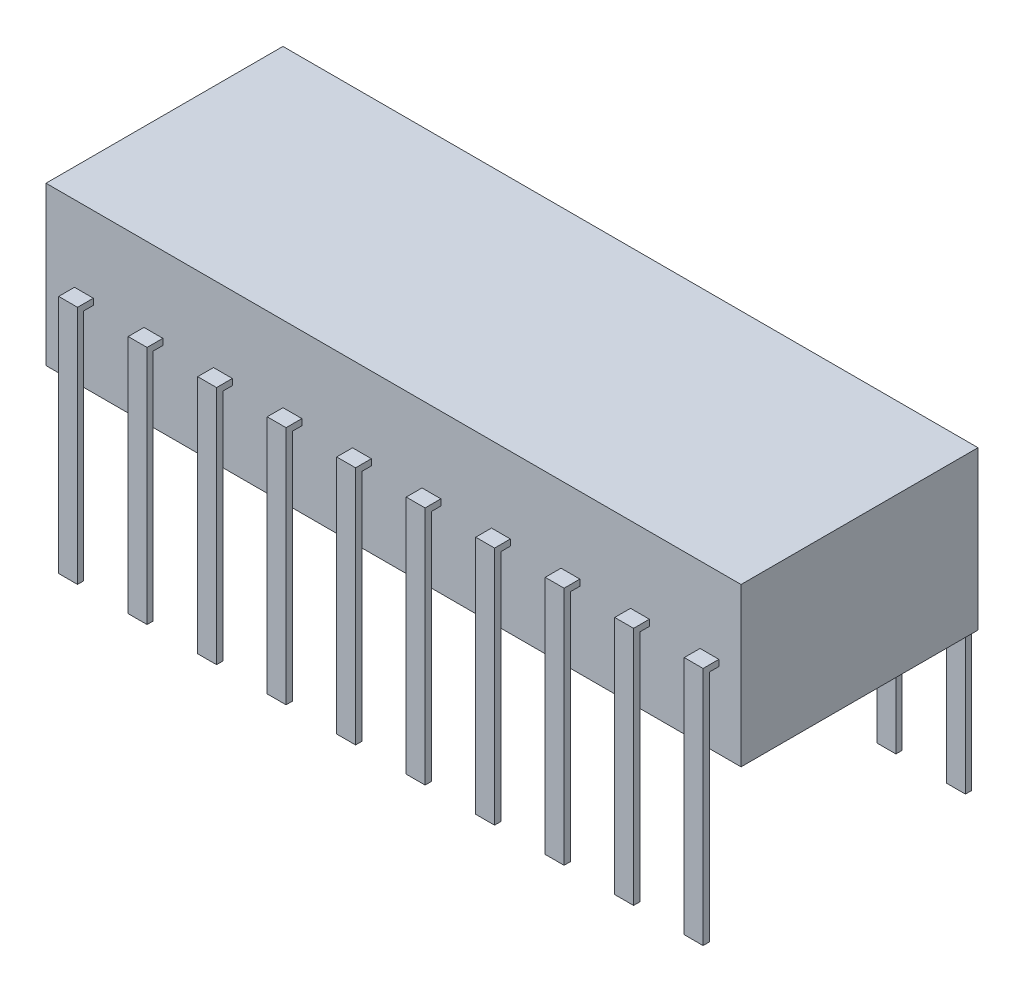
SolidWorks part; units mm, degrees
ref_plane "Front Plane" through (0, 0, 0) normal (0, 0, 1) x (1, 0, 0)
ref_plane "Top Plane" through (0, 0, 0) normal (0, 1, 0) x (1, 0, 0)
ref_plane "Right Plane" through (0, 0, 0) normal (1, 0, 0) x (0, 0, -1)
sketch "Sketch2" plane through (0, 5.9229, 0) normal (0, 0, 1) x (1, 0, 0)
  line L1 (22, 5) -> (0, 5)
  line L2 (22, 5) -> (22, 0)
  line L3 (22, 0) -> (0, 0)
  line L4 (0, 5) -> (0, 0)
  line L5 (0.7, 2.6) -> (1.3, 2.6)
  line L6 (0.7, 2.6) -> (0.7, 2.4)
  line L7 (0.7, 2.4) -> (1.3, 2.4)
  line L8 (1.3, 2.6) -> (1.3, 2.4)
extrude "Boss-Extrude2" add sketch "Sketch2" along normal blind 7.5 contours L2 L1 L4 L3
sketch "Sketch11" plane through (0, 0, 0) normal (0, 0, 1) x (1, 0, 0)
  line L1 (22, 5.9229) -> (21, 5.9229)
  line L2 (22, 5.9229) -> (22, 8.422)
  line L3 (22, 8.422) -> (21, 8.422)
  line L4 (21, 5.9229) -> (21, 8.422)
  point P5 (0, 0)
  point P6 (0, 0)
  point P7 (20.1763, 5.9229)
  point P8 (22, 5.9229)
  point P9 (22, 5.9229)
  point P10 (20.155, 6.7317)
  point P11 (20.1479, 7.0227)
  point P12 (20.4034, 8.3855)
  point P13 (19.5659, 8.5771)
  point P14 (0, 0)
  point P15 (0, 0)
  point P16 (0, 0)
sketch "Sketch16" plane through (0, 0, 0) normal (0, 0, 1) x (1, 0, 0)
  line L1 (21.2984, 8.5206) -> (20.7016, 8.5206)
  line L2 (21.2984, 8.5206) -> (21.2984, 8.3234)
  line L3 (21.2984, 8.3234) -> (20.7016, 8.3234)
  line L4 (20.7016, 8.5206) -> (20.7016, 8.3234)
  line L5 (21.2984, 8.5206) -> (20.7016, 8.3234) construction
  line L6 (21.2984, 8.3234) -> (20.7016, 8.5206) construction
  point P0 (21, 8.422)
extrude "Boss-Extrude6" add sketch "Sketch16" against normal blind 0.5
sketch "Sketch17" plane through (0, 8.3234, 0) normal (0, -1, 0) x (1, 0, 0)
  line L0 (21.2984, -0.5) -> (21.2984, 0) construction
  line L1 (20.7016, -0.5) -> (21.2984, -0.5)
  line L2 (20.7016, -0.5) -> (20.7016, -0.3039)
  line L3 (20.7016, -0.3039) -> (21.2984, -0.3039)
  line L4 (21.2984, -0.5) -> (21.2984, -0.3039)
extrude "Boss-Extrude7" add sketch "Sketch17" along normal blind 7.4
sketch "Sketch18" plane through (0, 0, 0) normal (0, 1, 0) x (1, 0, 0)
  line L1 (21.2984, 0.5) -> (0.6993, 0.5)
  line L2 (21.2984, 0.5) -> (21.2984, -8)
  line L3 (21.2984, -8) -> (0.6993, -8)
  line L4 (0.6993, 0.5) -> (0.6993, -8)
pattern_linear "LPattern2" count 10 spacing 2.2 along (-1, 0, 0) of "Boss-Extrude6", "Boss-Extrude7"
sketch "Sketch21" plane through (0, 10.9229, 0) normal (0, 1, 0) x (1, 0, 0)
  line L0 (0, -3.75) -> (22, -3.75)
  line L1 (0, -7.5) -> (0, 0) construction
  line L2 (22, -7.5) -> (22, 0) construction
  point P6 (500000, 20092.7317)
sketch "Sketch22" plane through (22, 0, 0) normal (1, 0, 0) x (0, 0, -1)
  line L0 (-3.75, 10.9229) -> (-3.75, 5.9229)
  line L1 (-7.5, 10.9229) -> (0, 10.9229) construction
  line L2 (-7.5, 5.9229) -> (0, 5.9229) construction
ref_plane "Plane6" through (0, 0, 3.75) normal (0, 0, -1) x (-1, 0, 0)
mirror "Mirror1" about plane through (0, 0, 3.75) normal (0, 0, -1) of "LPattern2", "Boss-Extrude6", "Boss-Extrude7"
